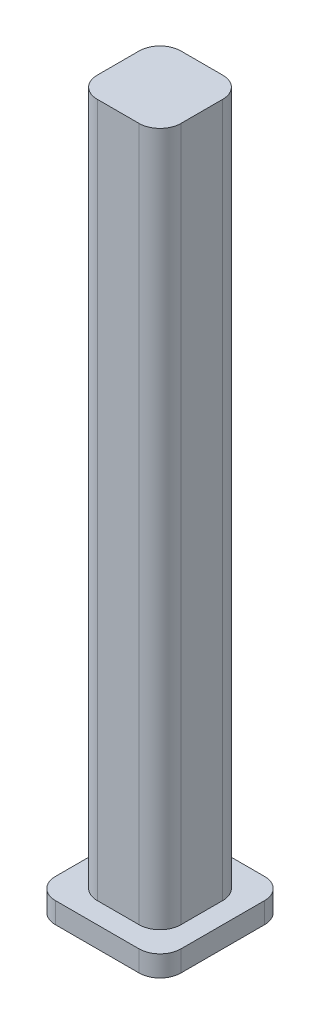
SolidWorks part; units mm, degrees
ref_plane "Front Plane" through (0, 0, 0) normal (0, 0, 1) x (1, 0, 0)
ref_plane "Top Plane" through (0, 0, 0) normal (0, 1, 0) x (1, 0, 0)
ref_plane "Right Plane" through (0, 0, 0) normal (1, 0, 0) x (0, 0, -1)
sketch "Sketch1" plane through (0, 0, 0) normal (0, 1, 0) x (1, 0, 0)
  line L1 (-30, -30) -> (30, -30)
  line L2 (-30, -30) -> (-30, 30)
  line L3 (-30, 30) -> (30, 30)
  line L4 (30, -30) -> (30, 30)
  line L5 (-30, -30) -> (30, 30) construction
  line L6 (-30, 30) -> (30, -30) construction
  point P0 (0, 0)
  dimension "D1" = 60
extrude "Boss-Extrude1" add sketch "Sketch1" along normal blind 10
sketch "Sketch2" plane through (0, 0, 0) normal (0, 1, 0) x (1, 0, 0)
  line L1 (-20, -20) -> (20, -20)
  line L2 (-20, -20) -> (-20, 20)
  line L3 (-20, 20) -> (20, 20)
  line L4 (20, -20) -> (20, 20)
  line L5 (-20, -20) -> (20, 20) construction
  line L6 (-20, 20) -> (20, -20) construction
  point P0 (0, 0)
  dimension "D1" = 40
extrude "Boss-Extrude2" add sketch "Sketch2" along normal blind 341.832
fillet "Fillet1" radius 10 8 edges at (30, 5, -30) (-30, 5, -30) (-30, 5, 30) (30, 5, 30) (20, 175.916, -20) (20, 175.916, 20) (-20, 175.916, -20) (-20, 175.916, 20)
